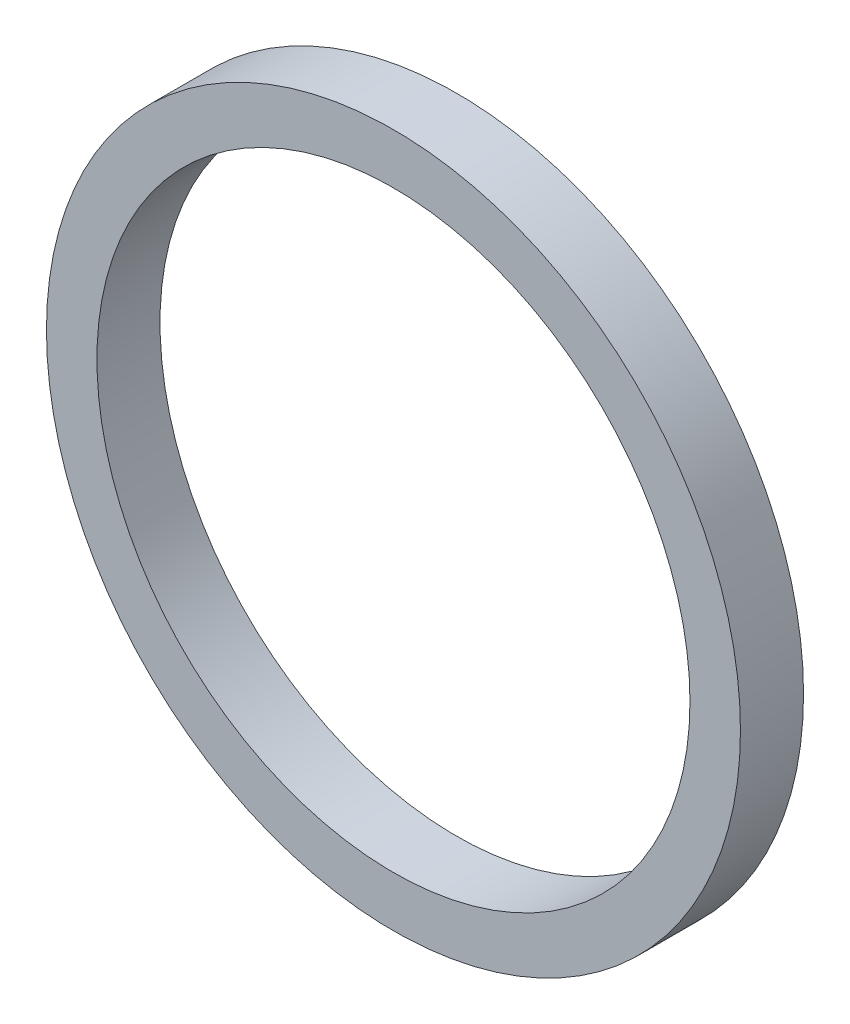
SolidWorks part; units mm, degrees
ref_plane "Front Plane" through (0, 0, 0) normal (0, 0, 1) x (1, 0, 0)
ref_plane "Top Plane" through (0, 0, 0) normal (0, 1, 0) x (1, 0, 0)
ref_plane "Right Plane" through (0, 0, 0) normal (1, 0, 0) x (0, 0, -1)
sketch "Sketch1" plane through (0, 0, 0) normal (0, 0, 1) x (1, 0, 0)
  circle A0 centre (0, 0) radius 14.1
  circle A1 centre (0, 0) radius 16.5
  dimension "D1" = 28.2
  dimension "D2" = 33
extrude "Boss-Extrude1" add sketch "Sketch1" along normal blind 3
